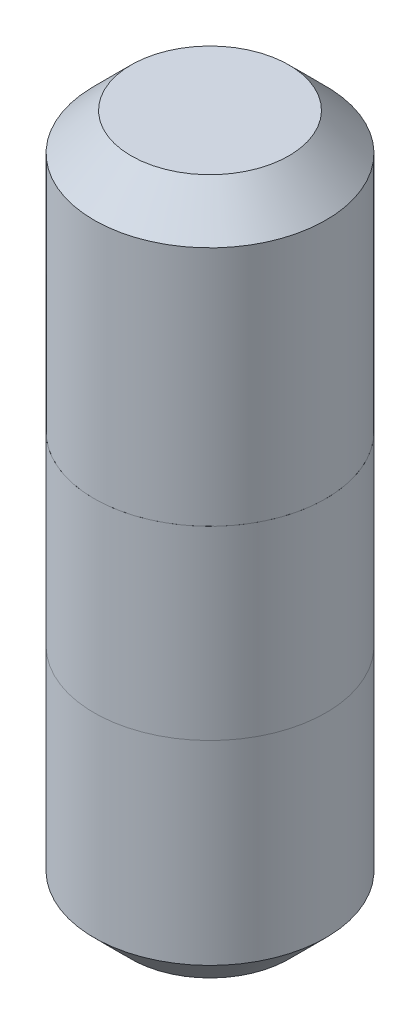
SolidWorks part; units mm, degrees
material "Простая углеродистая сталь"
ref_plane "Спереди" through (0, 0, 0) normal (0, 0, 1) x (1, 0, 0)
ref_plane "Сверху" through (0, 0, 0) normal (0, 1, 0) x (1, 0, 0)
ref_plane "Справа" through (0, 0, 0) normal (1, 0, 0) x (0, 0, -1)
sketch "Эскиз1" plane through (0, 0, 0) normal (0, 1, 0) x (1, 0, 0)
  circle A0 centre (0, 0) radius 5
  dimension "D1" = 10
extrude "Бобышка-Вытянуть1" add sketch "Эскиз1" along normal blind 12
cosmetic thread "Условное изображение резьбы2" [suppressed] parameters "D2"=9.656
cosmetic thread "Условное изображение резьбы3" parameters "D2"=8.619
cosmetic thread "Условное изображение резьбы6" [suppressed] parameters "D2"=4.891
cosmetic thread "Условное изображение резьбы8" [suppressed] parameters "D2"=6.619
cosmetic thread "Условное изображение резьбы9" [suppressed] parameters "D2"=26.158
cosmetic thread "Условное изображение резьбы11" [suppressed] parameters "D2"=20.704
cosmetic thread "Условное изображение резьбы13" [suppressed] parameters "D2"=23.704
sketch "Эскиз2" plane through (0, 0, 0) normal (0, -1, 0) x (1, 0, 0)
  circle A0 centre (0, 0) radius 5
  circle A1 centre (0, 0) radius 5 construction
extrude "Бобышка-Вытянуть2" add sketch "Эскиз2" along normal blind 8 separate body
sketch "Эскиз3" plane through (0, -8, 0) normal (0, -1, 0) x (1, 0, 0)
  circle A0 centre (0, 0) radius 5
  dimension "D1" = 10
extrude "Бобышка-Вытянуть3" add sketch "Эскиз3" along normal blind 10
cosmetic thread "Условное изображение резьбы1" [suppressed] parameters "D2"=10.344
cosmetic thread "Условное изображение резьбы4" parameters "D2"=8.619
cosmetic thread "Условное изображение резьбы5" [suppressed] parameters "D2"=4.891
cosmetic thread "Условное изображение резьбы7" [suppressed] parameters "D2"=6.619
cosmetic thread "Условное изображение резьбы10" [suppressed] parameters "D2"=26.158
cosmetic thread "Условное изображение резьбы12" [suppressed] parameters "D2"=20.704
cosmetic thread "Условное изображение резьбы14" [suppressed] parameters "D2"=23.704
chamfer "Фаска2" distance 1.6 angle 45 1 edges at (0, 12, 5)
chamfer "Фаска3" distance 1.6 angle 45 1 edges at (0, -18, -5)
equation "\"D1@Эскиз3\"= \"D1@Эскиз1\""
